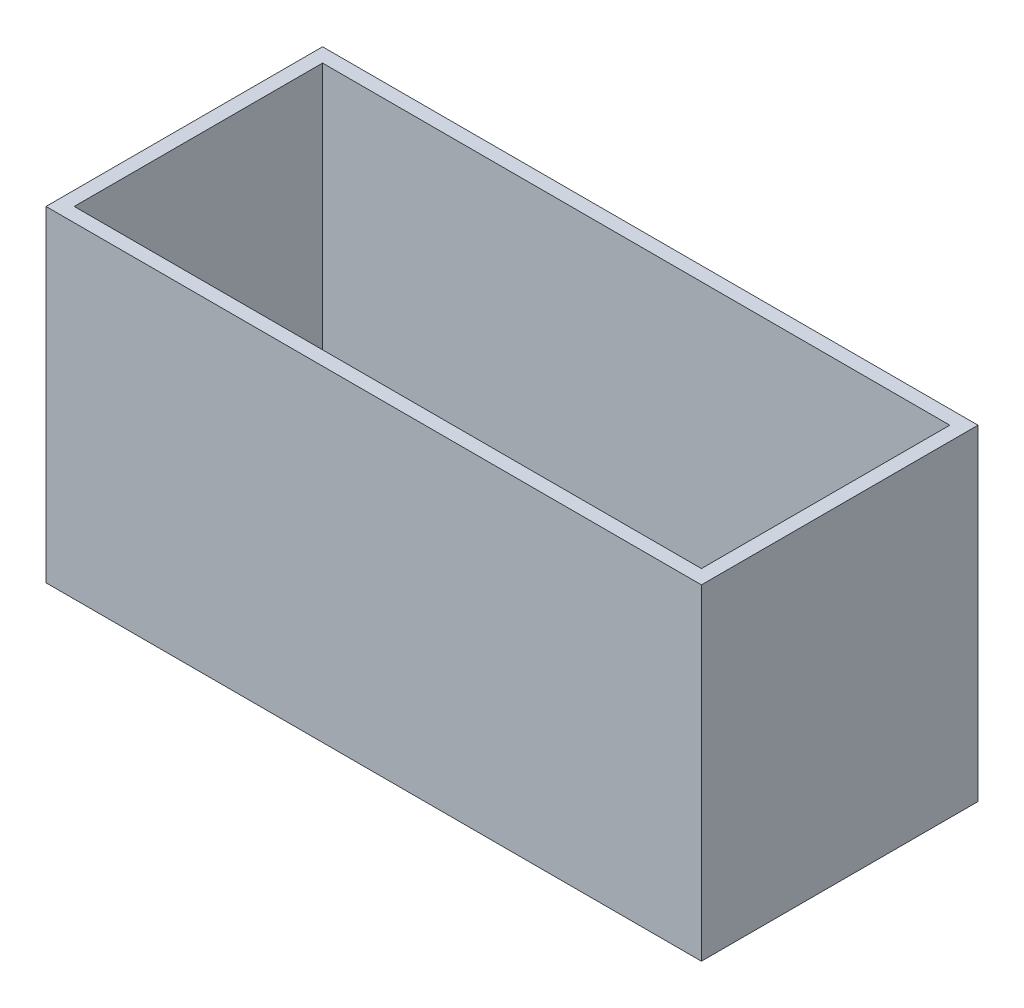
SolidWorks part; units mm, degrees
ref_plane "Front Plane" through (0, 0, 0) normal (0, 0, 1) x (1, 0, 0)
ref_plane "Top Plane" through (0, 0, 0) normal (0, 1, 0) x (1, 0, 0)
ref_plane "Right Plane" through (0, 0, 0) normal (1, 0, 0) x (0, 0, -1)
sketch "Sketch1" plane through (0, 0, 0) normal (0, 1, 0) x (1, 0, 0)
  line L1 (-464.5, -196) -> (464.5, -196)
  line L2 (-464.5, -196) -> (-464.5, 196)
  line L3 (-464.5, 196) -> (464.5, 196)
  line L4 (464.5, -196) -> (464.5, 196)
  line L5 (-464.5, -196) -> (464.5, 196) construction
  line L6 (-464.5, 196) -> (464.5, -196) construction
  point P0 (0, 0)
extrude "Bottom Plate" add sketch "Sketch1" along normal blind 20
sketch "Sketch2" plane through (0, 0, 0) normal (0, 1, 0) x (1, 0, 0)
  line L1 (-464.5, 176) -> (464.5, 176)
  line L2 (-464.5, 176) -> (-464.5, 196)
  line L3 (-464.5, 196) -> (464.5, 196)
  line L4 (464.5, 176) -> (464.5, 196)
  line L5 (-464.5, 176) -> (464.5, 196) construction
  line L6 (-464.5, 196) -> (464.5, 176) construction
  point P0 (0, 186)
extrude "Left Wall" add sketch "Sketch2" along normal blind 462
sketch "Sketch3" plane through (0, 0, 0) normal (0, 1, 0) x (1, 0, 0)
  line L0 (464.5, -196) -> (464.5, 176) construction
  line L1 (-464.5, -196) -> (464.5, -196)
  line L2 (-464.5, -196) -> (-464.5, -176)
  line L3 (-464.5, -176) -> (464.5, -176)
  line L4 (464.5, -196) -> (464.5, -176)
  line L5 (-464.5, -196) -> (464.5, -176) construction
  line L6 (-464.5, -176) -> (464.5, -196) construction
  point P0 (0, -186)
extrude "Right Wall" add sketch "Sketch3" along normal blind 462
sketch "Sketch4" plane through (0, 0, 0) normal (0, 1, 0) x (1, 0, 0)
  line L1 (444.5, -176) -> (464.5, -176)
  line L2 (444.5, -176) -> (444.5, 176)
  line L3 (444.5, 176) -> (464.5, 176)
  line L4 (464.5, -176) -> (464.5, 176)
  line L5 (444.5, -176) -> (464.5, 176) construction
  line L6 (444.5, 176) -> (464.5, -176) construction
  point P0 (454.5, 0)
extrude "Back Wall" add sketch "Sketch4" along normal blind 462
sketch "Sketch5" plane through (0, 0, 0) normal (0, 1, 0) x (1, 0, 0)
  line L0 (-464.5, 176) -> (444.5, 176) construction
  line L1 (-464.5, -176) -> (-444.5, -176)
  line L2 (-464.5, -176) -> (-464.5, 176)
  line L3 (-464.5, 176) -> (-444.5, 176)
  line L4 (-444.5, -176) -> (-444.5, 176)
  line L5 (-464.5, -176) -> (-444.5, 176) construction
  line L6 (-464.5, 176) -> (-444.5, -176) construction
  point P0 (-454.5, 0)
extrude "Front Wall" add sketch "Sketch5" along normal blind 462
